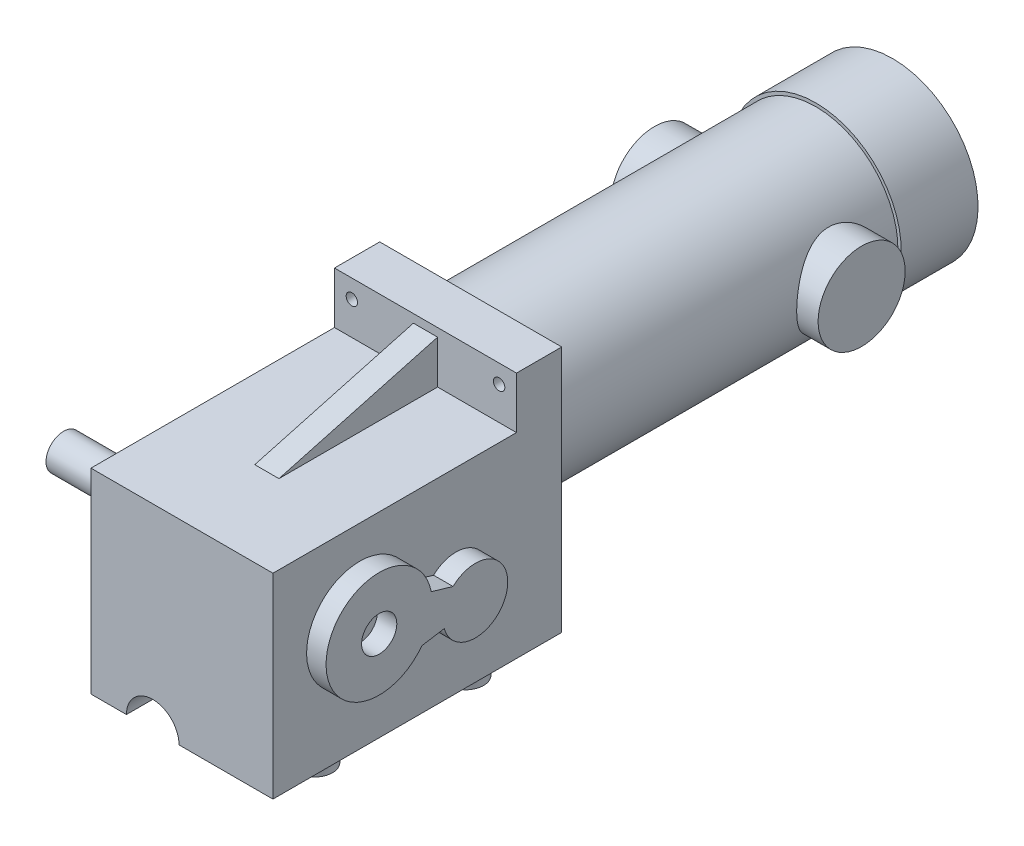
SolidWorks part; units mm, degrees
ref_plane "Front Plane" through (0, 0, 0) normal (0, 0, 1) x (1, 0, 0)
ref_plane "Top Plane" through (0, 0, 0) normal (0, 1, 0) x (1, 0, 0)
ref_plane "Right Plane" through (0, 0, 0) normal (1, 0, 0) x (0, 0, -1)
sketch "Sketch1" plane through (0, 0, 0) normal (0, 0, 1) x (1, 0, 0)
  line L1 (43.942, 47.244) -> (-43.942, 47.244)
  line L2 (43.942, 47.244) -> (43.942, -47.244)
  line L3 (43.942, -47.244) -> (-43.942, -47.244)
  line L4 (-43.942, 47.244) -> (-43.942, -47.244)
  line L5 (43.942, 47.244) -> (-43.942, -47.244) construction
  line L6 (43.942, -47.244) -> (-43.942, 47.244) construction
  point P0 (0, 0)
  dimension "D1" = 87.884
  dimension "D2" = 94.488
extrude "Boss-Extrude1" add sketch "Sketch1" against normal blind 139.446
sketch "Sketch2" plane through (-43.942, 0, 0) normal (1, 0, 0) x (0, 0, -1)
  line L0 (139.446, -47.244) -> (0, -47.244) construction
  line L1 (0, -47.244) -> (0, 47.244) construction
  circle A0 centre (41.91, 5.6388) radius 8.5
  dimension "D3" = 17
  dimension "D1" = 52.8828
  dimension "D2" = 41.91
extrude "Boss-Extrude2" add sketch "Sketch2" against normal blind 55.118
sketch "Sketch3" plane through (0, 0, -139.446) normal (0, 0, -1) x (-1, 0, 0)
  line L0 (43.942, -47.244) -> (-43.942, -47.244) construction
  circle A0 centre (0, 27.686) radius 39.6875
  dimension "D1" = 79.375
  dimension "D2" = 74.93
extrude "Boss-Extrude3" add sketch "Sketch3" along normal blind 176.022
sketch "Sketch4" plane through (0, 0, -139.446) normal (0, 0, 1) x (1, 0, 0)
  line L0 (43.942, 47.244) -> (-43.942, 47.244) construction
  line L1 (-43.942, 72.136) -> (43.942, 72.136)
  line L2 (-43.942, 72.136) -> (-43.942, 47.244)
  line L3 (43.942, 47.244) -> (-43.942, 47.244)
  line L4 (43.942, 72.136) -> (43.942, 47.244)
  line L5 (-43.942, -47.244) -> (43.942, -47.244) construction
  point P0 (0, 27.686)
  point P1 (0, 27.686)
  dimension "D1" = 119.38
extrude "Boss-Extrude4" add sketch "Sketch4" along normal blind 21.844
sketch "Sketch5" plane through (0, 0, 0) normal (1, 0, 0) x (0, 0, -1)
  line L0 (41.0006, 47.244) -> (117.602, 68.1184)
  line L1 (117.602, 47.244) -> (0, 47.244) construction
  line L3 (117.602, 47.244) -> (117.602, 68.1184)
  line L4 (117.602, 47.244) -> (41.0006, 47.244)
  line L5 (117.602, 47.244) -> (117.602, 72.136) construction
extrude "Boss-Extrude5" add sketch "Sketch5" along normal mid plane 11.684
sketch "Sketch6" plane through (-43.942, 0, 0) normal (1, 0, 0) x (0, 0, -1)
  line L0 (67.0628, 10.6851) -> (77.5828, 7.6054)
  line L1 (73.3188, -7.886) -> (62.5178, -9.6401)
  arc A0 (67.0628, 10.6851) -> (62.5178, -9.6401) centre (41.91, 5.6388) ccw
  arc A1 (73.3188, -7.886) -> (77.5828, 7.6054) centre (88.3672, -3.6956) ccw
  dimension "D1" = 51.308
  dimension "D2" = 31.242
extrude "not verified extrude" add sketch "Sketch6" against normal blind 10.033
sketch "Sketch8" plane through (0, 0, -139.446) normal (0, 0, -1) x (-1, 0, 0)
  line L1 (35.56, -7.874) -> (-35.56, -7.874) construction
  line L2 (35.56, -7.874) -> (35.56, 63.246) construction
  line L3 (35.56, 63.246) -> (-35.56, 63.246) construction
  line L4 (-35.56, -7.874) -> (-35.56, 63.246) construction
  line L5 (35.56, -7.874) -> (-35.56, 63.246) construction
  line L6 (35.56, 63.246) -> (-35.56, -7.874) construction
  circle A0 centre (-35.56, 63.246) radius 2.75
  circle A1 centre (35.56, 63.246) radius 2.75
  circle A2 centre (35.56, -7.874) radius 2.75
  circle A3 centre (-35.56, -7.874) radius 2.75
  point P0 (0, 27.686)
  point P1 (0, 27.686)
  dimension "D1" = 5.5
  dimension "D2" = 71.12
  dimension "D3" = 71.12
extrude "Cut-Extrude2" cut sketch "Sketch8" against normal blind 25.4
sketch "Sketch7" plane through (0, 0, 0) normal (0, 0, 1) x (1, 0, 0)
  line L0 (-43.942, -47.244) -> (43.942, -47.244) construction
  line L2 (-53.975, 31.2928) -> (-53.975, -20.0152) construction
  circle A0 centre (-14.097, -47.244) radius 12.7
  dimension "D1" = 25.4
  dimension "D2" = 39.878
extrude "change for opposite motor" cut sketch "Sketch7" against normal through all
sketch "Sketch9" plane through (0, -47.244, 0) normal (0, -1, 0) x (1, 0, 0)
  line L0 (-53.975, -16.256) -> (-53.975, -67.0628) construction
  line L1 (-1.397, 0) -> (-26.797, 0) construction
  circle A0 centre (8.001, -7.9756) radius 3
  circle A1 centre (8.001, -68.3768) radius 3
  circle A2 centre (8.001, -128.778) radius 3
  circle A3 centre (-36.449, -128.778) radius 3
  circle A4 centre (-36.449, -68.3768) radius 3
  circle A5 centre (-36.449, -7.9756) radius 3
  dimension "D5" = 6
  dimension "D1" = 61.976
  dimension "D2" = 60.4012
  dimension "D3" = 60.4012
  dimension "D4" = 7.9756
  dimension "D6" = 44.45
extrude "Cut-Extrude3" cut sketch "Sketch9" against normal blind 12.7
sketch "Sketch10" plane through (0, -47.244, 0) normal (0, -1, 0) x (1, 0, 0)
  line L0 (-53.975, -16.256) -> (-53.975, -67.0628) construction
  line L1 (-43.942, 0) -> (-26.797, 0) construction
  circle A0 centre (32.639, -31.496) radius 8.5725
  circle A1 centre (32.639, -104.4448) radius 8.5725
  dimension "D1" = 17.145
  dimension "D2" = 86.614
  dimension "D3" = 31.496
  dimension "D4" = 72.9488
extrude "Boss-Extrude6" add sketch "Sketch10" along normal blind 6.096
sketch "Sketch11" plane through (0, 0, -315.468) normal (0, 0, -1) x (-1, 0, 0)
  line L0 (-26.5, 27.686) -> (26.5, 27.686) construction
  circle A0 centre (-26.5, 27.686) radius 1.5
  circle A1 centre (26.5, 27.686) radius 1.5
  point P0 (0, 27.686)
  point P6 (0, 27.686)
  dimension "D1" = 53
  dimension "D2" = 3
extrude "Cut-Extrude4" cut sketch "Sketch11" against normal blind 25.4
sketch "Sketch12" plane through (43.942, 0, 0) normal (1, 0, 0) x (0, 0, -1)
  line L0 (77.5828, 7.6054) -> (67.0628, 10.6851) construction
  line L1 (62.5178, -9.6401) -> (73.3188, -7.886) construction
  line L2 (77.5828, 7.6054) -> (67.0628, 10.6851)
  line L3 (62.5178, -9.6401) -> (73.3188, -7.886)
  arc A0 (67.0628, 10.6851) -> (62.5178, -9.6401) centre (41.91, 5.6388) ccw construction
  circle A1 centre (41.91, 5.6388) radius 8.5 construction
  arc A2 (73.3188, -7.886) -> (77.5828, 7.6054) centre (88.3672, -3.6956) ccw construction
  arc A3 (67.0628, 10.6851) -> (62.5178, -9.6401) centre (41.91, 5.6388) ccw
  circle A4 centre (41.91, 5.6388) radius 8.5
  arc A5 (73.3188, -7.886) -> (77.5828, 7.6054) centre (88.3672, -3.6956) ccw
extrude "Boss-Extrude7" add sketch "Sketch12" along normal blind 9.398
sketch "Sketch13" plane through (0, 0, 0) normal (1, 0, 0) x (0, 0, -1)
  line L0 (315.468, -12.0015) -> (315.468, 67.3735) construction
  line L1 (315.468, 67.3735) -> (139.446, 67.3735) construction
  line L2 (315.468, 27.686) -> (278.2125, 26.9725) construction
  circle A0 centre (278.2125, 26.9725) radius 21.0269
  dimension "D1" = 42.0538
  dimension "D2" = 37.2555
  dimension "D3" = 40.401
extrude "Boss-Extrude8" add sketch "Sketch13" along normal mid plane 100.0125
sketch "Sketch15" plane through (0, 0, -315.468) normal (0, 0, -1) x (-1, 0, 0)
  line L1 (-7.493, 35.179) -> (7.493, 35.179)
  line L2 (-7.493, 35.179) -> (-7.493, 20.193)
  line L3 (-7.493, 20.193) -> (7.493, 20.193)
  line L4 (7.493, 35.179) -> (7.493, 20.193)
  line L5 (-7.493, 35.179) -> (7.493, 20.193) construction
  line L6 (-7.493, 20.193) -> (7.493, 35.179) construction
  point P0 (0, 27.686)
  dimension "D1" = 14.986
extrude "Boss-Extrude9" add sketch "Sketch15" along normal blind 6.35
sketch "Sketch14" plane through (0, 0, -315.468) normal (0, 0, -1) x (-1, 0, 0)
  circle A0 centre (0, 27.686) radius 41.275
  dimension "D1" = 82.55
extrude "brake and end cap" add sketch "Sketch14" along normal blind 27.686 and the other way blind 9.398
